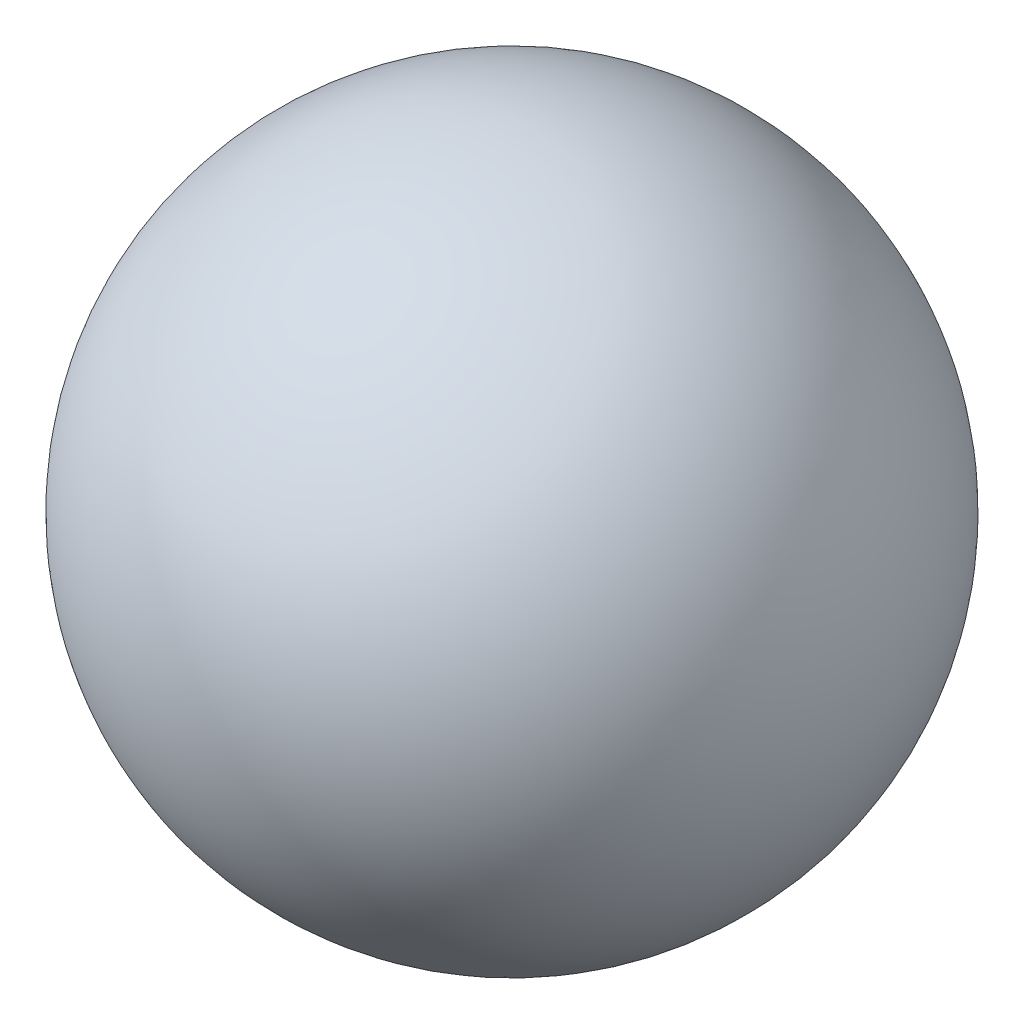
SolidWorks part; units mm, degrees
ref_plane "Front Plane" through (0, 0, 0) normal (0, 0, 1) x (1, 0, 0)
ref_plane "Top Plane" through (0, 0, 0) normal (0, 1, 0) x (1, 0, 0)
ref_plane "Right Plane" through (0, 0, 0) normal (1, 0, 0) x (0, 0, -1)
sketch "Sketch1" plane through (0, 0, 0) normal (0, 1, 0) x (1, 0, 0)
  line L0 (0, 119.2543) -> (0, -119.2543)
  arc A0 (0, -119.2543) -> (0, 119.2543) centre (0, 0) ccw
  dimension "D1" = 119.2543
revolve "Revolve1" add sketch "Sketch1" angle 360 about L0
